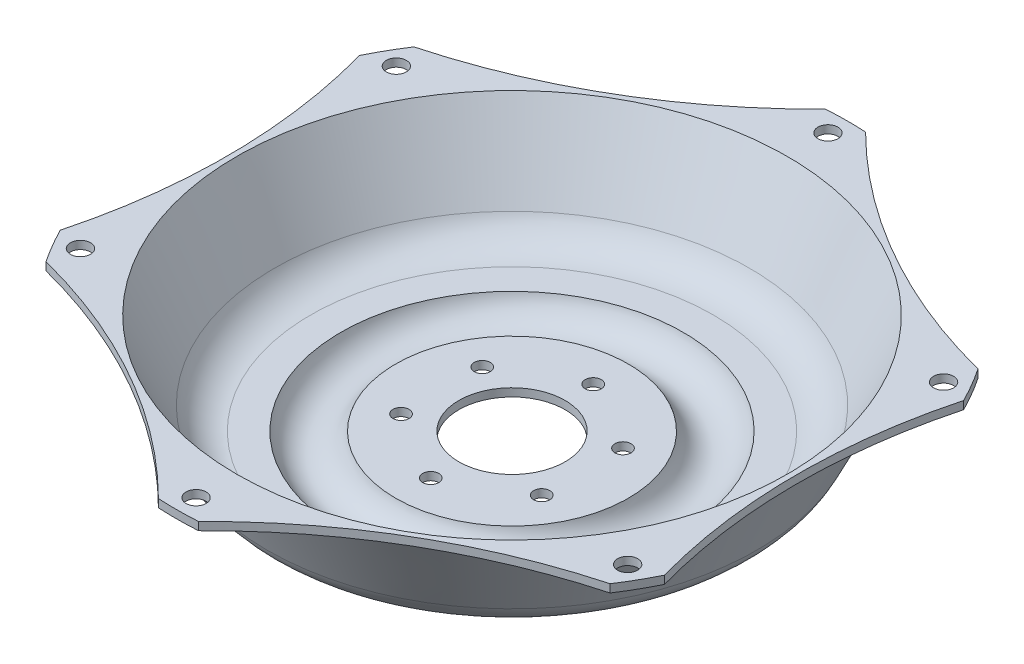
SolidWorks part; units mm, degrees
ref_plane "Front Plane" through (0, 0, 0) normal (0, 0, 1) x (1, 0, 0)
ref_plane "Top Plane" through (0, 0, 0) normal (0, 1, 0) x (1, 0, 0)
ref_plane "Right Plane" through (0, 0, 0) normal (1, 0, 0) x (0, 0, -1)
sketch "Sketch1" plane through (0, 0, 0) normal (0, 0, 1) x (1, 0, 0)
  line L0 (0, 0) -> (0, 186.3217) construction
  line L1 (53, 0) -> (116, 0)
  line L2 (170.7083, 0) -> (200.7083, 0)
  line L3 (236.6601, 22.4652) -> (274.4764, 100)
  line L4 (274.4764, 100) -> (335, 100)
  arc A0 (116, 0) -> (170.7083, 0) centre (143.3542, 8) ccw
  arc A1 (200.7083, 0) -> (236.6601, 22.4652) centre (200.7083, 40) ccw
  dimension "D4" = 28.5
  dimension "D6" = 40
  dimension "D9" = 335
  dimension "D1" = 53
  dimension "D2" = 63
  dimension "D3" = 8
  dimension "D5" = 30
  dimension "D7" = 100
  dimension "D8" = 116
surface "Surface-Revolve1" sketch "Sketch1" parameters "D1"=360
thicken "Thicken1" surfaces to thicken 101 thickness 8 parameters "D1"=8
sketch "Sketch2" plane through (0, 92, 0) normal (0, -1, 0) x (1, 0, 0)
  line L0 (0, 0) -> (0, 389.4558) construction
  arc A0 (-18, 334.5161) -> (-278.6408, 185.9685) centre (-420.9628, 738.6195) cw
  circle A1 centre (0, 0) radius 335 construction
  circle A2 centre (0, 0) radius 279.4753 construction
  circle A3 centre (0, 315) radius 10
  arc A4 (0, 335) -> (-278.6408, 185.9685) centre (0, 0) ccw
  circle M2 centre (0, 0) radius 335
  dimension "D3" = 20
  dimension "D1" = 18
  dimension "D2" = 300
  dimension "D4" = 315
extrude "Cut-Extrude1" cut sketch "Sketch2" against normal blind 10 contours A0 M2 | L0 A3 | A3 L0
pattern_circular "CirPattern1" count 6 every 60 about axis through (0, 0, 0) along (0, 1, 0) of "Cut-Extrude1"
sketch "Sketch3" plane through (0, -8, 0) normal (0, -1, 0) x (1, 0, 0)
  circle A0 centre (0, 81) radius 8
  dimension "D1" = 16
  dimension "D2" = 81
extrude "Cut-Extrude2" cut sketch "Sketch3" against normal blind 10
pattern_circular "CirPattern2" count 6 every 60 about axis through (0, 0, 0) along (0, 1, 0) of "Cut-Extrude2"
